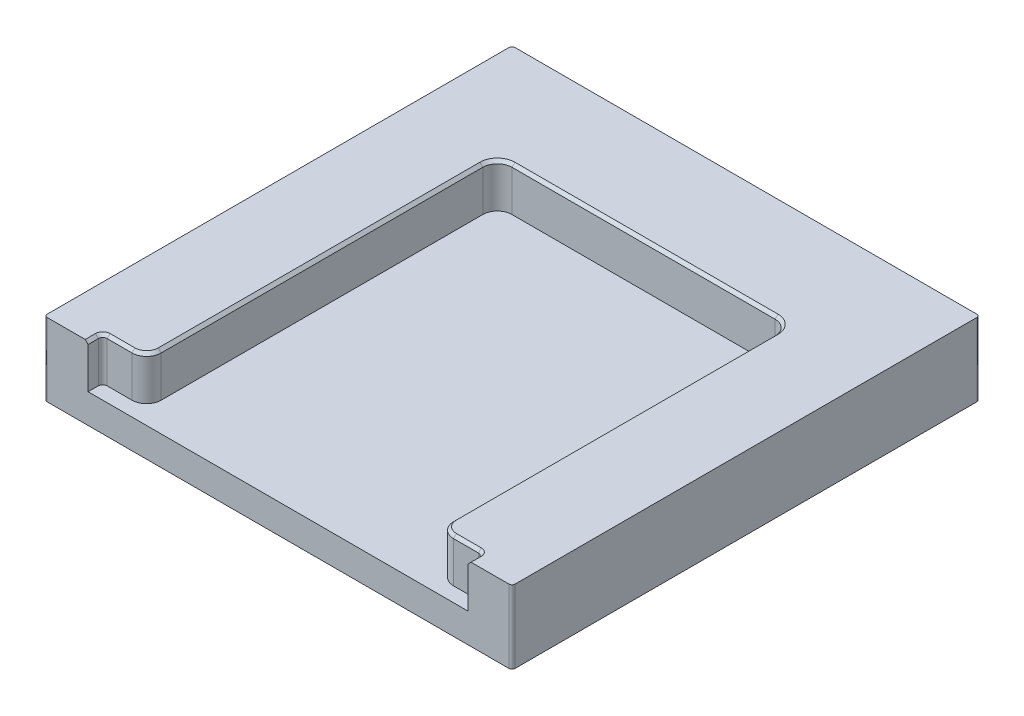
SolidWorks part; units mm, degrees
material "1060 合金"
ref_plane "前视基准面" through (0, 0, 0) normal (0, 0, 1) x (1, 0, 0)
ref_plane "上视基准面" through (0, 0, 0) normal (0, 1, 0) x (1, 0, 0)
ref_plane "右视基准面" through (0, 0, 0) normal (1, 0, 0) x (0, 0, -1)
sketch "草图1" plane through (0, 0, 0) normal (0, 1, 0) x (1, 0, 0)
  line L1 (-158, -160) -> (158, -160)
  line L2 (-160, -158) -> (-160, 158)
  line L3 (-158, 160) -> (158, 160)
  line L4 (160, -158) -> (160, 158)
  line L5 (-160, -160) -> (160, 160) construction
  line L6 (-160, 160) -> (160, -160) construction
  arc A0 (160, -158) -> (158, -160) centre (158, -158) cw
  arc A1 (-158, -160) -> (-160, -158) centre (-158, -158) cw
  arc A2 (160, 158) -> (158, 160) centre (158, 158) ccw
  arc A3 (-158, 160) -> (-160, 158) centre (-158, 158) ccw
  point P0 (0, 0)
  dimension "D3" = 2
  dimension "D1" = 320
  dimension "D2" = 320
extrude "凸台-拉伸1" add sketch "草图1" against normal blind 50
sketch "草图2" plane through (0, 0, 0) normal (0, 1, 0) x (1, 0, 0)
  line L0 (0, 160) -> (0, -160) construction
  line L5 (130, -153) -> (130, -160)
  line L6 (110, -150) -> (127, -150)
  line L7 (158, 160) -> (-158, 160) construction
  line L8 (-158, -160) -> (158, -160) construction
  line L9 (90, 90) -> (-90, 90)
  line L10 (-100, 80) -> (-100, -140)
  line L11 (-110, -150) -> (-127, -150)
  line L12 (-130, -153) -> (-130, -160)
  line L13 (-130, -160) -> (130, -160)
  line L14 (100, 80) -> (100, -140)
  arc A0 (110, -150) -> (100, -140) centre (110, -140) cw
  arc A1 (-100, -140) -> (-110, -150) centre (-110, -140) cw
  arc A2 (100, 80) -> (90, 90) centre (90, 80) ccw
  arc A3 (-90, 90) -> (-100, 80) centre (-90, 80) ccw
  arc A4 (130, -153) -> (127, -150) centre (127, -153) ccw
  arc A5 (-127, -150) -> (-130, -153) centre (-127, -153) ccw
  point P0 (0, 0)
  point P19 (0, 90)
  point P21 (100, -150)
  point P24 (-100, -150)
  point P27 (100, 90)
  point P30 (-100, 90)
  point P33 (130, -150)
  point P36 (-130, -150)
  dimension "D1" = 10
  dimension "D2" = 3
  dimension "D3" = 100
  dimension "D4" = 130
  dimension "D5" = 250
  dimension "D6" = 10
extrude "切除-拉伸2" cut sketch "草图2" against normal blind 30
chamfer "倒角1" distance 2 angle 45 13 edges at (130, 0, 156.5) (129.1213, 0, 150.8787) (118.5, 0, 150) (102.9289, 0, 147.0711) (100, 0, 30) (97.0711, 0, -87.0711) (0, 0, -90) (-97.0711, 0, -87.0711) (-100, 0, 30) (-102.9289, 0, 147.0711) (-118.5, 0, 150) (-129.1213, 0, 150.8787) (-130, 0, 156.5)
